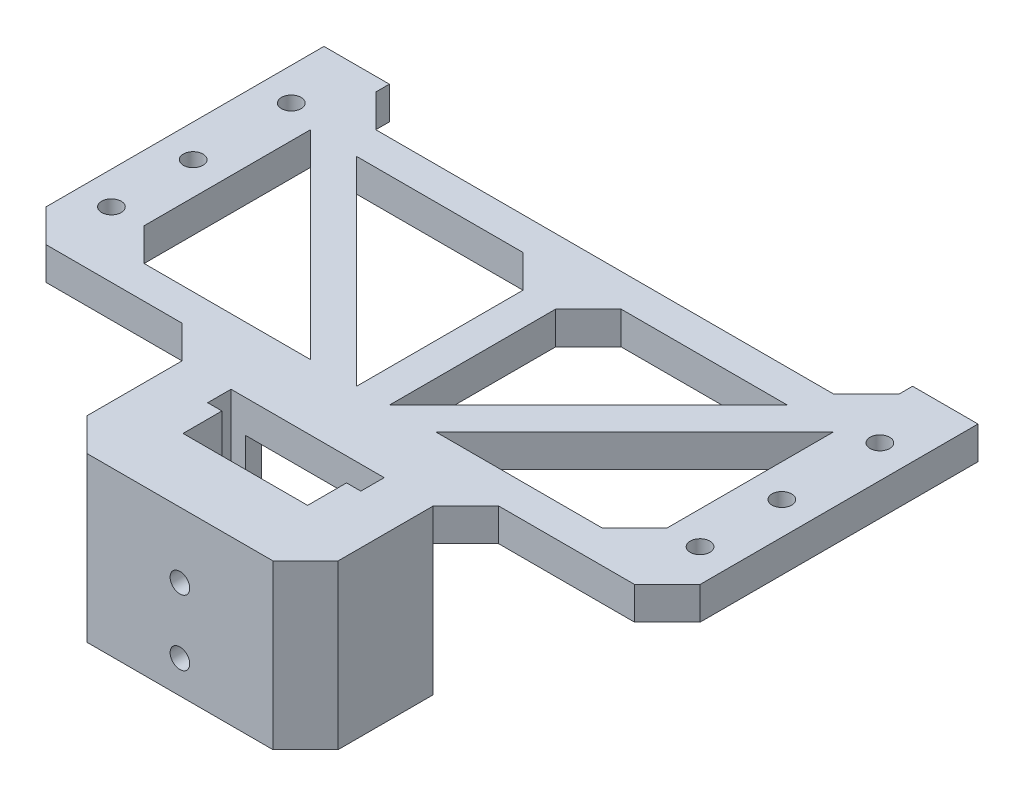
SolidWorks part; units mm, degrees
ref_plane "Front Plane" through (0, 0, 0) normal (0, 0, 1) x (1, 0, 0)
ref_plane "Top Plane" through (0, 0, 0) normal (0, 1, 0) x (1, 0, 0)
ref_plane "Right Plane" through (0, 0, 0) normal (1, 0, 0) x (0, 0, -1)
sketch "Sketch1" plane through (0, 0, 0) normal (0, 1, 0) x (1, 0, 0)
  line L0 (-14.2078, 0) -> (14.2078, 0)
  line L3 (50, 29.525) -> (50, 72.025)
  line L4 (50, 72.025) -> (40, 72.025)
  line L5 (40, 72.025) -> (40, 69.9539)
  line L8 (0, 72.025) -> (0, 0) construction
  line L15 (-9.525, 10) -> (9.525, 10)
  line L16 (9.525, 10) -> (9.525, 15.9531)
  line L17 (9.525, 15.9531) -> (11.7078, 15.9531)
  line L18 (11.7078, 15.9531) -> (11.7078, 19.525)
  line L19 (11.7078, 19.525) -> (-11.7078, 19.525)
  line L20 (-11.7078, 15.9531) -> (-11.7078, 19.525)
  line L21 (-9.525, 15.9531) -> (-11.7078, 15.9531)
  line L22 (-9.525, 10) -> (-9.525, 15.9531)
  line L24 (19.2078, 5) -> (19.2078, 19.525)
  line L25 (19.2078, 19.525) -> (24.2078, 24.525)
  line L26 (24.2078, 24.525) -> (45, 24.525)
  line L27 (45, 24.525) -> (50, 29.525)
  line L31 (-24.2078, 24.525) -> (-45, 24.525)
  line L32 (-19.2078, 19.525) -> (-24.2078, 24.525)
  line L33 (-19.2078, 5) -> (-19.2078, 19.525)
  line L37 (19.2078, 5) -> (14.2078, 0)
  line L38 (-19.2078, 5) -> (-14.2078, 0)
  line L40 (35, 64.9539) -> (-35, 64.9539)
  line L43 (35, 64.9539) -> (40, 69.9539)
  line L46 (2.5, 54.9539) -> (2.5, 29.525)
  line L47 (2.5, 29.525) -> (32.9289, 59.9539)
  line L48 (32.9289, 59.9539) -> (7.5, 59.9539)
  line L49 (40, 59.9539) -> (9.5711, 29.525)
  line L50 (9.5711, 29.525) -> (35, 29.525)
  line L51 (40, 34.525) -> (40, 59.9539)
  line L52 (7.5, 59.9539) -> (7.5, 64.9539) construction
  line L53 (35, 29.525) -> (35, 24.525) construction
  line L54 (32.9289, 59.9539) -> (36.4645, 56.4184) construction
  line L55 (-40, 34.525) -> (-40, 59.9539)
  line L56 (-40, 34.525) -> (-35, 29.525)
  line L57 (-9.5711, 29.525) -> (-35, 29.525)
  line L64 (-35, 64.9539) -> (-40, 69.9539)
  line L65 (-45, 24.525) -> (-50, 29.525)
  line L66 (-40, 72.025) -> (-40, 69.9539)
  line L67 (-50, 72.025) -> (-40, 72.025)
  line L68 (-50, 29.525) -> (-50, 72.025)
  line L69 (7.5, 59.9539) -> (2.5, 54.9539)
  line L70 (40, 34.525) -> (35, 29.525)
  line L71 (-40, 59.9539) -> (-9.5711, 29.525)
  line L72 (-2.5, 29.525) -> (-32.9289, 59.9539)
  line L73 (-2.5, 54.9539) -> (-2.5, 29.525)
  line L74 (-7.5, 59.9539) -> (-2.5, 54.9539)
  line L75 (-32.9289, 59.9539) -> (-7.5, 59.9539)
  circle A0 centre (45, 34.525) radius 1.5
  circle A1 centre (45, 47.025) radius 1.5
  circle A2 centre (45, 62.025) radius 1.5
  circle A6 centre (-45, 62.025) radius 1.5
  circle A7 centre (-45, 47.025) radius 1.5
  circle A8 centre (-45, 34.525) radius 1.5
  point P1 (7.6349, 29.525)
  point P9 (45, 72.025)
  point P24 (0, 19.525)
  point P27 (0, 10)
  point P35 (6.8325, 56.5106)
  point P42 (32.2094, 29.525)
  point P43 (40, 65.954)
  point P48 (34.8173, 60.6379)
  point P65 (0, 64.9539)
  point P68 (-45, 72.025)
  point P73 (-37.2373, 57.1912)
  point P74 (0, 0)
  point P75 (40, 59.7821)
  point P76 (0, 72.025)
  point P77 (0, 25.8321)
  dimension "D8" = 3
  dimension "D1" = 3.5719
  dimension "D2" = 5.9531
  dimension "D3" = 19.05
  dimension "D4" = 23.4156
  dimension "D5" = 10
  dimension "D6" = 40
  dimension "D7" = 10
  dimension "D9" = 12.5
  dimension "D10" = 15
  dimension "D11" = 10
  dimension "D12" = 10
  dimension "D13" = 5
  dimension "D14" = 7.5
  dimension "D15" = 5
  dimension "D16" = 45
  dimension "D17" = 5
  dimension "D18" = 45
  dimension "D19" = 5
  dimension "D20" = 5
  dimension "D21" = 5
extrude "Boss-Extrude1" add sketch "Sketch1" along normal blind 5
sketch "Sketch2" plane through (0, 0, 0) normal (0, 1, 0) x (1, 0, 0)
  line L1 (-11.7078, 15.9531) -> (-9.525, 15.9531) construction
  line L4 (-9.525, 10) -> (9.525, 10) construction
  line L5 (-9.525, 15.9531) -> (-9.525, 10) construction
  line L6 (-11.7078, 19.525) -> (-11.7078, 15.9531) construction
  line L7 (19.2078, 19.525) -> (19.2078, 5)
  line L8 (-11.7078, 15.9531) -> (-9.525, 15.9531)
  line L9 (19.2078, 5) -> (14.2078, 0)
  line L10 (16.7078, 22.025) -> (19.2078, 19.525)
  line L11 (-9.525, 10) -> (9.525, 10)
  line L12 (-9.525, 15.9531) -> (-9.525, 10)
  line L13 (-11.7078, 19.525) -> (-11.7078, 15.9531)
  line L14 (-11.7078, 19.525) -> (-9.525, 19.525)
  line L15 (11.7078, 19.525) -> (-11.7078, 19.525) construction
  line L16 (-9.525, 19.525) -> (-9.525, 22.025)
  line L17 (-9.525, 22.025) -> (-16.7078, 22.025)
  line L18 (-16.7078, 22.025) -> (-19.2078, 19.525)
  line L21 (-14.2078, 0) -> (14.2078, 0) construction
  line L22 (-19.2078, 5) -> (-14.2078, 0) construction
  line L23 (-19.2078, 19.525) -> (-19.2078, 5) construction
  line L24 (9.525, 22.025) -> (16.7078, 22.025)
  line L25 (9.525, 19.525) -> (9.525, 22.025)
  line L26 (-14.2078, 0) -> (14.2078, 0)
  line L27 (-19.2078, 5) -> (-14.2078, 0)
  line L28 (-19.2078, 19.525) -> (-19.2078, 5)
  line L29 (0, 0) -> (0, 10) construction
  line L30 (11.7078, 19.525) -> (9.525, 19.525)
  line L31 (11.7078, 19.525) -> (11.7078, 15.9531)
  line L32 (9.525, 15.9531) -> (9.525, 10)
  line L33 (11.7078, 15.9531) -> (9.525, 15.9531)
  point P22 (0, 0)
  dimension "D1" = 135
  dimension "D2" = 2.5
extrude "Boss-Extrude2" add sketch "Sketch2" against normal blind 20
sketch "Sketch3" plane through (0, 0, -10) normal (0, 0, -1) x (-1, 0, 0)
  circle A0 centre (0, -15) radius 1.5
  circle A1 centre (0, -5) radius 1.5
  point P4 (0, 0)
  point P6 (0, 0)
  point P7 (0, 0)
  point P8 (0, -4.7426)
  dimension "D2" = 3
  dimension "D1" = 10
  dimension "D3" = 5
extrude "Cut-Extrude1" cut sketch "Sketch3" against normal up to next
